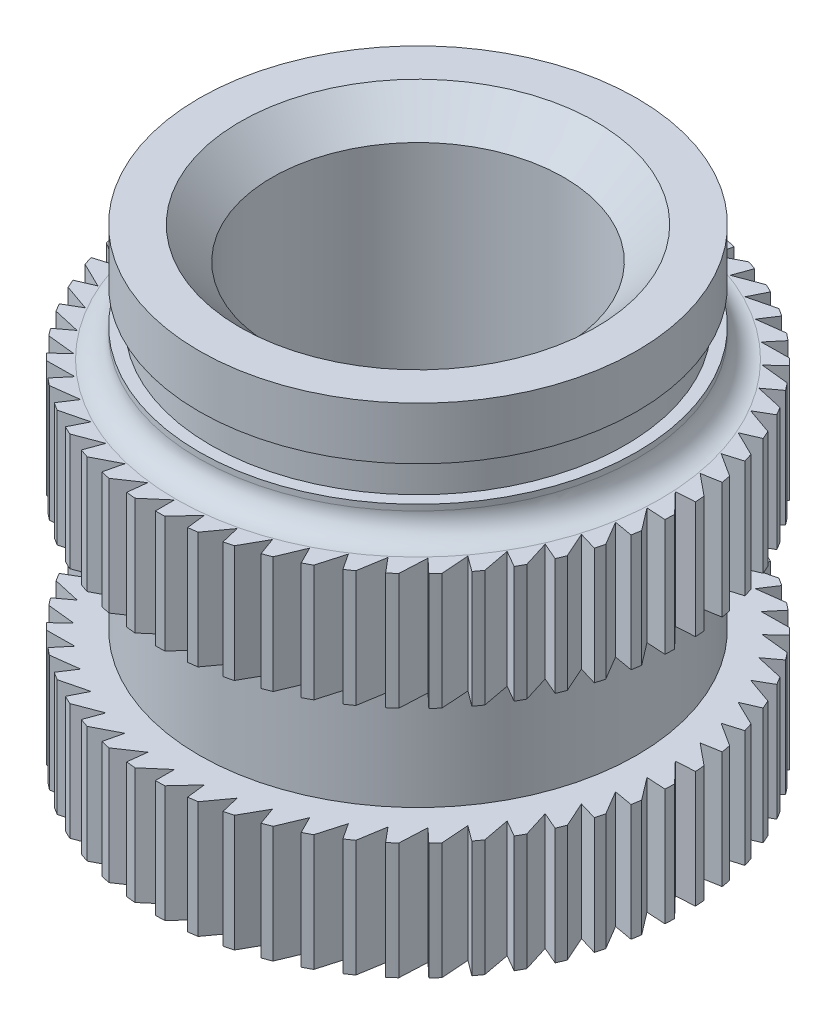
SolidWorks part; units mm, degrees
ref_plane "前视基准面" through (0, 0, 0) normal (0, 0, 1) x (1, 0, 0)
ref_plane "上视基准面" through (0, 0, 0) normal (0, 1, 0) x (1, 0, 0)
ref_plane "右视基准面" through (0, 0, 0) normal (1, 0, 0) x (0, 0, -1)
other "Configuration Table"
sketch "草图1" plane through (0, 0, 0) normal (1, 0, 0) x (0, 0, -1)
  line L0 (0, 0) -> (-0.2, 0) construction
  line L1 (-1.875, 4) -> (-1.875, 3)
  line L2 (-0.2, 0) -> (-2.25, 0)
  line L3 (-0.2, 0) -> (-0.2, 4)
  line L4 (-0.2, 4) -> (-1.875, 4)
  line L5 (-2.25, 0) -> (-2.25, 1)
  line L6 (-1.875, 3) -> (-2.25, 3)
  line L7 (-2.25, 2) -> (-1.875, 2)
  line L8 (-1.875, 2) -> (-1.875, 1)
  line L9 (-1.875, 1) -> (-2.25, 1)
  line L10 (0, 0) -> (0, 0.9108) construction
  line L11 (-2.25, 2) -> (-2.25, 3)
  dimension "D1" = 2.25
  dimension "D2" = 0.2
  dimension "D4" = 1
  dimension "D5" = 1
revolve "旋转2" add sketch "草图1" angle 360 about L10
hole_wizard "M3 螺纹孔1" positions "3D草图3" profile "草图4" tap size "M3" standard "GB" end condition through all
sketch3d "3D草图3"
  line L0 (0, 4, 0) -> (0, 3, 0) construction
  point P0 (0, 4, 0)
sketch "草图4" plane through (0, 4, 0) normal (1, 0, 0) x (0, 0, 1)
  line L0 (0, 0) -> (0, 4)
  line L1 (0, 4) -> (1.25, 4)
  line L2 (1.25, 4) -> (1.25, 0.275)
  line L3 (1.25, 0.275) -> (1.525, 0)
  line L5 (1.525, 0) -> (0, 0)
  line L6 (-1.25, 0.275) -> (-1.525, 0) construction
  line L11 (0, -6.35) -> (0, 107.95) construction
  dimension "通孔螺纹孔钻头直径" = 2.5
  dimension "通孔螺纹孔钻头深度" = 4
  dimension "近端锥形沉头孔直径" = 3.05
  dimension "近端锥形沉头孔角度" = 90
cosmetic thread "孔螺蚊线1" parameters "D2"=3
fillet "圆角2" radius 0.2 1 edges at (0, 3, -1.875)
ref_plane "基准面1" through (0, 3.25, 0) normal (0, 1, 0) x (1, 0, 0)
sketch "草图6" plane through (0, 3.25, 0) normal (0, 1, 0) x (1, 0, 0)
  circle A0 centre (0, 0) radius 1.875
  circle A1 centre (0, 0) radius 1.775
  dimension "D1" = 3.75
  dimension "D2" = 0.1
extrude "切除-拉伸2" cut sketch "草图6" along normal blind 0.3
sketch "草图5" plane through (0, 3, 0) normal (0, 1, 0) x (1, 0, 0)
  line L0 (0, -2.25) -> (0, 0) construction
  line L1 (-0.1817, -2.2426) -> (0, -2.0865)
  line L2 (0, -2.0865) -> (0, -2.25)
  line L3 (-0.2422, -2.0724) -> (-0.2612, -2.2348)
  line L4 (-0.4409, -2.2064) -> (-0.2422, -2.0724)
  line L5 (-0.4812, -2.0303) -> (-0.5189, -2.1894)
  line L6 (-0.694, -2.1403) -> (-0.4812, -2.0303)
  line L7 (-0.7136, -1.9607) -> (-0.7695, -2.1143)
  line L8 (-0.9378, -2.0452) -> (-0.7136, -1.9607)
  line L9 (-0.9364, -1.8646) -> (-1.0098, -2.0107)
  line L10 (-1.1689, -1.9225) -> (-0.9364, -1.8646)
  line L11 (-1.1466, -1.7433) -> (-1.2364, -1.8798)
  line L12 (-1.3842, -1.7738) -> (-1.1466, -1.7433)
  line L13 (-1.3412, -1.5984) -> (-1.4463, -1.7236)
  line L14 (-1.5808, -1.6011) -> (-1.3412, -1.5984)
  line L15 (-1.5177, -1.4319) -> (-1.6366, -1.544)
  line L16 (-1.756, -1.4068) -> (-1.5177, -1.4319)
  line L17 (-1.6737, -1.246) -> (-1.8048, -1.3436)
  line L18 (-1.9074, -1.1934) -> (-1.6737, -1.246)
  line L19 (-1.807, -1.0433) -> (-1.9486, -1.125)
  line L20 (-2.0331, -0.9639) -> (-1.807, -1.0433)
  line L21 (-1.9159, -0.8264) -> (-2.066, -0.8912)
  line L22 (-2.1312, -0.7214) -> (-1.9159, -0.8264)
  line L23 (-1.9989, -0.5984) -> (-2.1555, -0.6453)
  line L24 (-2.2006, -0.4691) -> (-1.9989, -0.5984)
  line L25 (-2.0548, -0.3623) -> (-2.2158, -0.3907)
  line L26 (-2.2401, -0.2104) -> (-2.0548, -0.3623)
  line L27 (-2.083, -0.1213) -> (-2.2462, -0.1308)
  line L28 (-2.2494, 0.051) -> (-2.083, -0.1213)
  line L29 (-2.083, 0.1213) -> (-2.2462, 0.1308)
  line L30 (-2.2283, 0.3118) -> (-2.083, 0.1213)
  line L31 (-2.0548, 0.3623) -> (-2.2158, 0.3907)
  line L32 (-2.177, 0.5684) -> (-2.0548, 0.3623)
  line L33 (-1.9989, 0.5984) -> (-2.1555, 0.6453)
  line L34 (-2.0963, 0.8173) -> (-1.9989, 0.5984)
  line L35 (-1.9159, 0.8264) -> (-2.066, 0.8912)
  line L36 (-1.9872, 1.0552) -> (-1.9159, 0.8264)
  line L37 (-1.807, 1.0433) -> (-1.9486, 1.125)
  line L38 (-1.8513, 1.2787) -> (-1.807, 1.0433)
  line L39 (-1.6737, 1.246) -> (-1.8048, 1.3436)
  line L40 (-1.6903, 1.485) -> (-1.6737, 1.246)
  line L41 (-1.5177, 1.4319) -> (-1.6366, 1.544)
  line L42 (-1.5065, 1.6712) -> (-1.5177, 1.4319)
  line L43 (-1.3412, 1.5984) -> (-1.4463, 1.7236)
  line L44 (-1.3023, 1.8348) -> (-1.3412, 1.5984)
  line L45 (-1.1466, 1.7433) -> (-1.2364, 1.8798)
  line L46 (-1.0805, 1.9736) -> (-1.1466, 1.7433)
  line L47 (-0.9364, 1.8646) -> (-1.0098, 2.0107)
  line L48 (-0.8441, 2.0857) -> (-0.9364, 1.8646)
  line L49 (-0.7136, 1.9607) -> (-0.7695, 2.1143)
  line L50 (-0.5962, 2.1696) -> (-0.7136, 1.9607)
  line L51 (-0.4812, 2.0303) -> (-0.5189, 2.1894)
  line L52 (-0.3403, 2.2241) -> (-0.4812, 2.0303)
  line L53 (-0.2422, 2.0724) -> (-0.2612, 2.2348)
  line L54 (-0.0798, 2.2486) -> (-0.2422, 2.0724)
  line L55 (0, 2.0865) -> (0, 2.25)
  line L56 (0.1817, 2.2426) -> (0, 2.0865)
  line L57 (0.2422, 2.0724) -> (0.2612, 2.2348)
  line L58 (0.4409, 2.2064) -> (0.2422, 2.0724)
  line L59 (0.4812, 2.0303) -> (0.5189, 2.1894)
  line L60 (0.694, 2.1403) -> (0.4812, 2.0303)
  line L61 (0.7136, 1.9607) -> (0.7695, 2.1143)
  line L62 (0.9378, 2.0452) -> (0.7136, 1.9607)
  line L63 (0.9364, 1.8646) -> (1.0098, 2.0107)
  line L64 (1.1689, 1.9225) -> (0.9364, 1.8646)
  line L65 (1.1466, 1.7433) -> (1.2364, 1.8798)
  line L66 (1.3842, 1.7738) -> (1.1466, 1.7433)
  line L67 (1.3412, 1.5984) -> (1.4463, 1.7236)
  line L68 (1.5808, 1.6011) -> (1.3412, 1.5984)
  line L69 (1.5177, 1.4319) -> (1.6366, 1.544)
  line L70 (1.756, 1.4068) -> (1.5177, 1.4319)
  line L71 (1.6737, 1.246) -> (1.8048, 1.3436)
  line L72 (1.9074, 1.1934) -> (1.6737, 1.246)
  line L73 (1.807, 1.0433) -> (1.9486, 1.125)
  line L74 (2.0331, 0.9639) -> (1.807, 1.0433)
  line L75 (1.9159, 0.8264) -> (2.066, 0.8912)
  line L76 (2.1312, 0.7214) -> (1.9159, 0.8264)
  line L77 (1.9989, 0.5984) -> (2.1555, 0.6453)
  line L78 (2.2006, 0.4691) -> (1.9989, 0.5984)
  line L79 (2.0548, 0.3623) -> (2.2158, 0.3907)
  line L80 (2.2401, 0.2104) -> (2.0548, 0.3623)
  line L81 (2.083, 0.1213) -> (2.2462, 0.1308)
  line L82 (2.2494, -0.051) -> (2.083, 0.1213)
  line L83 (2.083, -0.1213) -> (2.2462, -0.1308)
  line L84 (2.2283, -0.3118) -> (2.083, -0.1213)
  line L85 (2.0548, -0.3623) -> (2.2158, -0.3907)
  line L86 (2.177, -0.5684) -> (2.0548, -0.3623)
  line L87 (1.9989, -0.5984) -> (2.1555, -0.6453)
  line L88 (2.0963, -0.8173) -> (1.9989, -0.5984)
  line L89 (1.9159, -0.8264) -> (2.066, -0.8912)
  line L90 (1.9872, -1.0552) -> (1.9159, -0.8264)
  line L91 (1.807, -1.0433) -> (1.9486, -1.125)
  line L92 (1.8513, -1.2787) -> (1.807, -1.0433)
  line L93 (1.6737, -1.246) -> (1.8048, -1.3436)
  line L94 (1.6903, -1.485) -> (1.6737, -1.246)
  line L95 (1.5177, -1.4319) -> (1.6366, -1.544)
  line L96 (1.5065, -1.6712) -> (1.5177, -1.4319)
  line L97 (1.3412, -1.5984) -> (1.4463, -1.7236)
  line L98 (1.3023, -1.8348) -> (1.3412, -1.5984)
  line L99 (1.1466, -1.7433) -> (1.2364, -1.8798)
  line L100 (1.0805, -1.9736) -> (1.1466, -1.7433)
  line L101 (0.9364, -1.8646) -> (1.0098, -2.0107)
  line L102 (0.8441, -2.0857) -> (0.9364, -1.8646)
  line L103 (0.7136, -1.9607) -> (0.7695, -2.1143)
  line L104 (0.5962, -2.1696) -> (0.7136, -1.9607)
  line L105 (0.4812, -2.0303) -> (0.5189, -2.1894)
  line L106 (0.3403, -2.2241) -> (0.4812, -2.0303)
  line L107 (0.2422, -2.0724) -> (0.2612, -2.2348)
  line L108 (0.0798, -2.2486) -> (0.2422, -2.0724)
  circle A0 centre (0, 0) radius 2.25 construction
  arc A1 (-0.1817, -2.2426) -> (0, -2.25) centre (0, 0) ccw
  arc A2 (-0.4409, -2.2064) -> (-0.2612, -2.2348) centre (0, 0) ccw
  arc A3 (-0.694, -2.1403) -> (-0.5189, -2.1894) centre (0, 0) ccw
  arc A4 (-0.9378, -2.0452) -> (-0.7695, -2.1143) centre (0, 0) ccw
  arc A5 (-1.1689, -1.9225) -> (-1.0098, -2.0107) centre (0, 0) ccw
  arc A6 (-1.3842, -1.7738) -> (-1.2364, -1.8798) centre (0, 0) ccw
  arc A7 (-1.5808, -1.6011) -> (-1.4463, -1.7236) centre (0, 0) ccw
  arc A8 (-1.756, -1.4068) -> (-1.6366, -1.544) centre (0, 0) ccw
  arc A9 (-1.9074, -1.1934) -> (-1.8048, -1.3436) centre (0, 0) ccw
  arc A10 (-2.0331, -0.9639) -> (-1.9486, -1.125) centre (0, 0) ccw
  arc A11 (-2.1312, -0.7214) -> (-2.066, -0.8912) centre (0, 0) ccw
  arc A12 (-2.2006, -0.4691) -> (-2.1555, -0.6453) centre (0, 0) ccw
  arc A13 (-2.2401, -0.2104) -> (-2.2158, -0.3907) centre (0, 0) ccw
  arc A14 (-2.2494, 0.051) -> (-2.2462, -0.1308) centre (0, 0) ccw
  arc A15 (-2.2283, 0.3118) -> (-2.2462, 0.1308) centre (0, 0) ccw
  arc A16 (-2.177, 0.5684) -> (-2.2158, 0.3907) centre (0, 0) ccw
  arc A17 (-2.0963, 0.8173) -> (-2.1555, 0.6453) centre (0, 0) ccw
  arc A18 (-1.9872, 1.0552) -> (-2.066, 0.8912) centre (0, 0) ccw
  arc A19 (-1.8513, 1.2787) -> (-1.9486, 1.125) centre (0, 0) ccw
  arc A20 (-1.6903, 1.485) -> (-1.8048, 1.3436) centre (0, 0) ccw
  arc A21 (-1.5065, 1.6712) -> (-1.6366, 1.544) centre (0, 0) ccw
  arc A22 (-1.3023, 1.8348) -> (-1.4463, 1.7236) centre (0, 0) ccw
  arc A23 (-1.0805, 1.9736) -> (-1.2364, 1.8798) centre (0, 0) ccw
  arc A24 (-0.8441, 2.0857) -> (-1.0098, 2.0107) centre (0, 0) ccw
  arc A25 (-0.5962, 2.1696) -> (-0.7695, 2.1143) centre (0, 0) ccw
  arc A26 (-0.3403, 2.2241) -> (-0.5189, 2.1894) centre (0, 0) ccw
  arc A27 (-0.0798, 2.2486) -> (-0.2612, 2.2348) centre (0, 0) ccw
  arc A28 (0.1817, 2.2426) -> (0, 2.25) centre (0, 0) ccw
  arc A29 (0.4409, 2.2064) -> (0.2612, 2.2348) centre (0, 0) ccw
  arc A30 (0.694, 2.1403) -> (0.5189, 2.1894) centre (0, 0) ccw
  arc A31 (0.9378, 2.0452) -> (0.7695, 2.1143) centre (0, 0) ccw
  arc A32 (1.1689, 1.9225) -> (1.0098, 2.0107) centre (0, 0) ccw
  arc A33 (1.3842, 1.7738) -> (1.2364, 1.8798) centre (0, 0) ccw
  arc A34 (1.5808, 1.6011) -> (1.4463, 1.7236) centre (0, 0) ccw
  arc A35 (1.756, 1.4068) -> (1.6366, 1.544) centre (0, 0) ccw
  arc A36 (1.9074, 1.1934) -> (1.8048, 1.3436) centre (0, 0) ccw
  arc A37 (2.0331, 0.9639) -> (1.9486, 1.125) centre (0, 0) ccw
  arc A38 (2.1312, 0.7214) -> (2.066, 0.8912) centre (0, 0) ccw
  arc A39 (2.2006, 0.4691) -> (2.1555, 0.6453) centre (0, 0) ccw
  arc A40 (2.2401, 0.2104) -> (2.2158, 0.3907) centre (0, 0) ccw
  arc A41 (2.2494, -0.051) -> (2.2462, 0.1308) centre (0, 0) ccw
  arc A42 (2.2283, -0.3118) -> (2.2462, -0.1308) centre (0, 0) ccw
  arc A43 (2.177, -0.5684) -> (2.2158, -0.3907) centre (0, 0) ccw
  arc A44 (2.0963, -0.8173) -> (2.1555, -0.6453) centre (0, 0) ccw
  arc A45 (1.9872, -1.0552) -> (2.066, -0.8912) centre (0, 0) ccw
  arc A46 (1.8513, -1.2787) -> (1.9486, -1.125) centre (0, 0) ccw
  arc A47 (1.6903, -1.485) -> (1.8048, -1.3436) centre (0, 0) ccw
  arc A48 (1.5065, -1.6712) -> (1.6366, -1.544) centre (0, 0) ccw
  arc A49 (1.3023, -1.8348) -> (1.4463, -1.7236) centre (0, 0) ccw
  arc A50 (1.0805, -1.9736) -> (1.2364, -1.8798) centre (0, 0) ccw
  arc A51 (0.8441, -2.0857) -> (1.0098, -2.0107) centre (0, 0) ccw
  arc A52 (0.5962, -2.1696) -> (0.7695, -2.1143) centre (0, 0) ccw
  arc A53 (0.3403, -2.2241) -> (0.5189, -2.1894) centre (0, 0) ccw
  arc A54 (0.0798, -2.2486) -> (0.2612, -2.2348) centre (0, 0) ccw
  point P168 (0, 0)
  dimension "D1" = 0.1817
  dimension "D2" = 0.1635
  dimension "D3" = 54
extrude "切除-拉伸1" cut sketch "草图5" against normal blind 10
